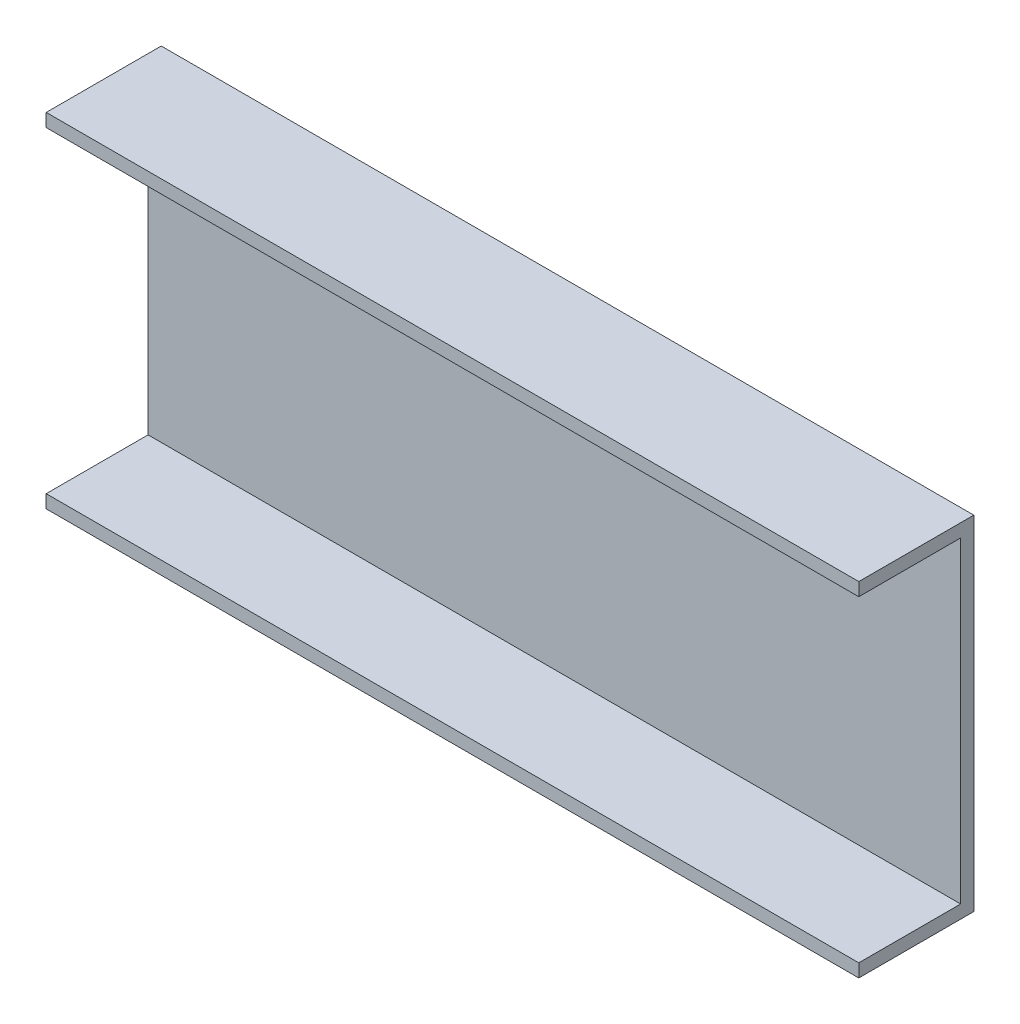
SolidWorks part; units mm, degrees
ref_plane "前视基准面" through (0, 0, 0) normal (0, 0, 1) x (1, 0, 0)
ref_plane "上视基准面" through (0, 0, 0) normal (0, 1, 0) x (1, 0, 0)
ref_plane "右视基准面" through (0, 0, 0) normal (1, 0, 0) x (0, 0, -1)
sketch "草图1" plane through (0, 0, 0) normal (0, 0, 1) x (1, 0, 0)
  line L1 (-355, 150) -> (355, 150)
  line L2 (-355, 150) -> (-355, -150)
  line L3 (-355, -150) -> (355, -150)
  line L4 (355, 150) -> (355, -150)
  line L5 (-355, 150) -> (355, -150) construction
  line L6 (-355, -150) -> (355, 150) construction
  point P0 (0, 0)
  dimension "D1" = 710
  dimension "D2" = 300
extrude "凸台-拉伸1" add sketch "草图1" along normal blind 11.5
sketch "草图3" plane through (0, 0, 11.5) normal (0, 0, 1) x (1, 0, 0)
  line L0 (-355, 138.5) -> (355, 138.5)
  line L1 (-355, 150) -> (-355, -150) construction
  line L2 (355, -150) -> (355, 150) construction
  line L3 (355, 150) -> (-355, 150) construction
  line L8 (355, -150) -> (355, 150)
  line L9 (355, 150) -> (-355, 150)
  line L10 (-355, 150) -> (-355, -150)
  line L11 (-355, -150) -> (355, -150)
  line L12 (355, 138.5) -> (355, 150)
  line L13 (355, 150) -> (-355, 150)
  line L14 (-355, 150) -> (-355, 138.5)
  dimension "D1" = 11.5
  dimension "D2" = 0
extrude "凸台-拉伸2" add sketch "草图3" along normal blind 89
mirror "镜向1" about plane through (0, 0, 0) normal (0, 1, 0) of "凸台-拉伸2"
